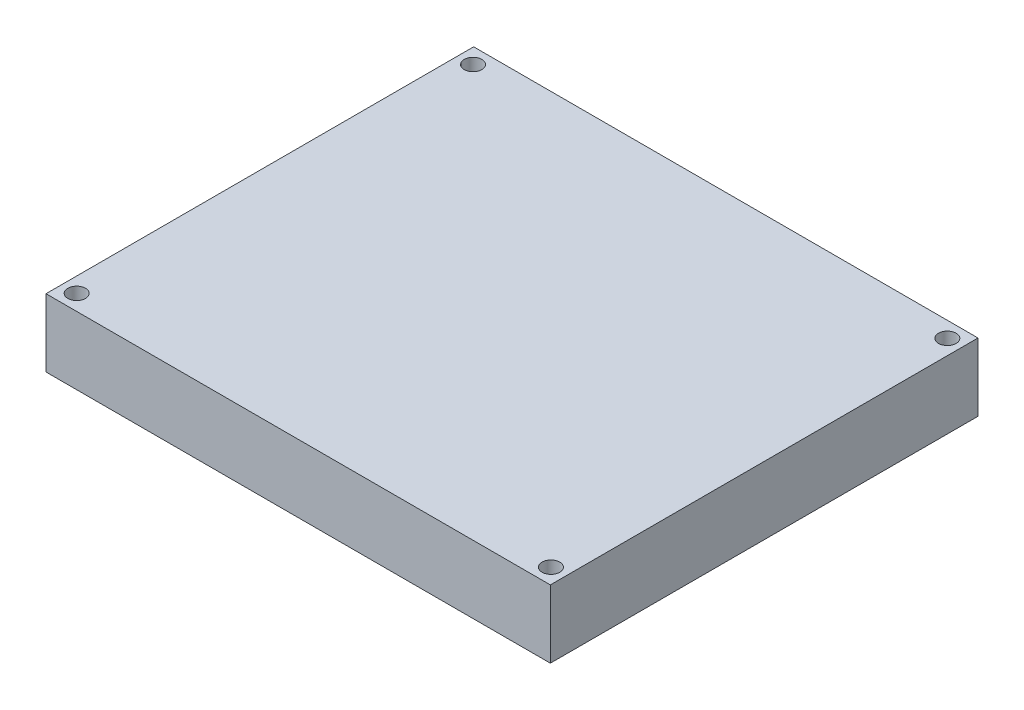
SolidWorks part; units mm, degrees
ref_plane "Front Plane" through (0, 0, 0) normal (0, 0, 1) x (1, 0, 0)
ref_plane "Top Plane" through (0, 0, 0) normal (0, 1, 0) x (1, 0, 0)
ref_plane "Right Plane" through (0, 0, 0) normal (1, 0, 0) x (0, 0, -1)
sketch "草图1" plane through (0, 0, 0) normal (0, 1, 0) x (1, 0, 0)
  line L0 (-42.75, 0) -> (54.8182, 0) construction
  line L1 (-42.75, 36.25) -> (42.75, 36.25)
  line L2 (-42.75, 36.25) -> (-42.75, -36.25)
  line L3 (-42.75, -36.25) -> (42.75, -36.25)
  line L4 (42.75, 36.25) -> (42.75, -36.25)
  line L5 (-42.75, 36.25) -> (42.75, -36.25) construction
  line L6 (-42.75, -36.25) -> (42.75, 36.25) construction
  line L7 (0, 36.25) -> (0, -19.4974) construction
  circle A0 centre (-40.2, 33.6) radius 1.5
  circle A1 centre (40.2, 33.6) radius 1.5
  circle A2 centre (40.2, -33.6) radius 1.5
  circle A3 centre (-40.2, -33.6) radius 1.5
  point P0 (0, 0)
  dimension "D3" = 3
  dimension "D5" = 2.55
  dimension "D1" = 85.5
  dimension "D2" = 72.5
  dimension "D4" = 2.65
extrude "凸台-拉伸1" add sketch "草图1" along normal blind 11.5
sketch "草图2" plane through (-42.75, 0, 0) normal (-1, 0, 0) x (0, 0, 1)
  line L1 (-13.9191, 8.8316) -> (24.3975, 8.8316)
  line L2 (-13.9191, 8.8316) -> (-13.9191, 1.064)
  line L3 (-13.9191, 1.064) -> (24.3975, 1.064)
  line L4 (24.3975, 8.8316) -> (24.3975, 1.064)
extrude "切除-拉伸1" cut sketch "草图2" against normal blind 3
